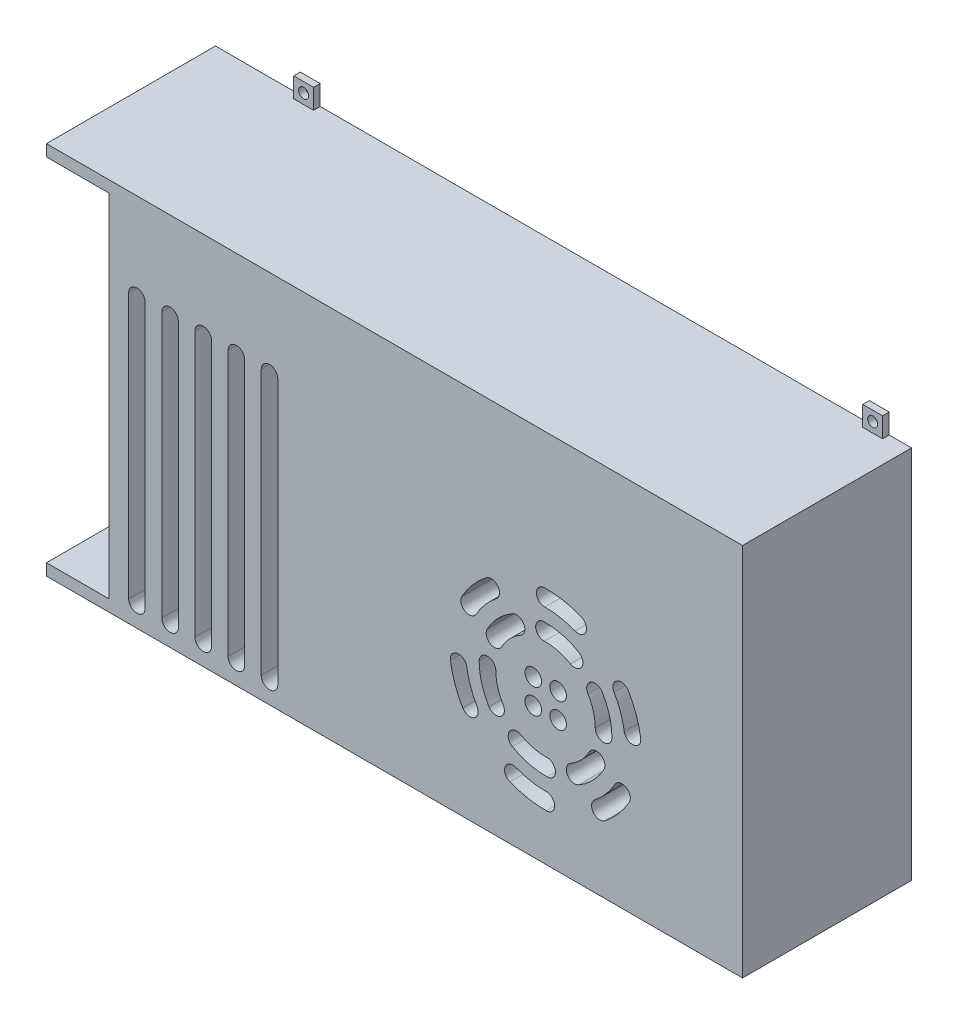
SolidWorks part; units mm, degrees
ref_plane "Plano frontal" through (0, 0, 0) normal (0, 0, 1) x (1, 0, 0)
ref_plane "Plano superior" through (0, 0, 0) normal (0, 1, 0) x (1, 0, 0)
ref_plane "Plano direito" through (0, 0, 0) normal (1, 0, 0) x (0, 0, -1)
sketch "Esboço1" plane through (0, 0, 0) normal (0, 0, 1) x (1, 0, 0)
  line L1 (-124.243, 56.5) -> (85.757, 56.5)
  line L2 (-124.243, 56.5) -> (-124.243, -56.5)
  line L3 (-124.243, -56.5) -> (85.757, -56.5)
  line L4 (85.757, 56.5) -> (85.757, -56.5)
  dimension "D1" = 210
  dimension "D2" = 56.5
  dimension "D3" = 56.5
extrude "Ressalto-extrusão1" add sketch "Esboço1" along normal blind 51
sketch "Esboço2" plane through (0, 0, 51) normal (0, 0, 1) x (1, 0, 0)
  arc A0 (33.8229, -0.4002) -> (25.9304, 1.6007) centre (26.3289, -13.394) ccw
  arc A1 (36.3349, 3.9553) -> (25.7969, 6.6268) centre (26.3289, -13.394) ccw
  arc A2 (35.2397, 8.8904) -> (26.1123, 10.605) centre (26.3289, -13.394) ccw
  arc A3 (37.0961, 13.533) -> (26.0672, 15.6048) centre (26.3289, -13.394) ccw
  arc A4 (25.7969, 6.6268) -> (25.9304, 1.6007) centre (25.8636, 4.1137) ccw
  arc A5 (33.8229, -0.4002) -> (36.3349, 3.9553) centre (35.0789, 1.7775) ccw
  arc A6 (41.3289, -13.3871) -> (39.1155, -5.5516) centre (26.3289, -13.394) ccw
  arc A7 (46.3568, -13.3848) -> (43.4014, -2.9228) centre (26.3289, -13.394) ccw
  arc A8 (43.4014, -2.9228) -> (39.1155, -5.5516) centre (41.2585, -4.2372) ccw
  arc A9 (41.3289, -13.3871) -> (46.3568, -13.3848) centre (43.8429, -13.386) ccw
  arc A10 (33.8349, -26.381) -> (39.514, -20.5463) centre (26.3289, -13.394) ccw
  arc A11 (36.3509, -30.7341) -> (43.9335, -22.9437) centre (26.3289, -13.394) ccw
  arc A12 (43.9335, -22.9437) -> (39.514, -20.5463) centre (41.7237, -21.745) ccw
  arc A13 (33.8349, -26.381) -> (36.3509, -30.7341) centre (35.0929, -28.5575) ccw
  arc A14 (18.8349, -26.3879) -> (26.7274, -28.3888) centre (26.3289, -13.394) ccw
  arc A15 (16.323, -30.7434) -> (26.861, -33.4149) centre (26.3289, -13.394) ccw
  arc A16 (26.861, -33.4149) -> (26.7274, -28.3888) centre (26.7942, -30.9018) ccw
  arc A17 (18.8349, -26.3879) -> (16.323, -30.7434) centre (17.5789, -28.5656) ccw
  arc A18 (11.3289, -13.401) -> (13.5424, -21.2365) centre (26.3289, -13.394) ccw
  arc A19 (6.301, -13.4033) -> (9.2564, -23.8653) centre (26.3289, -13.394) ccw
  arc A20 (9.2564, -23.8653) -> (13.5424, -21.2365) centre (11.3994, -22.5509) ccw
  arc A21 (11.3289, -13.401) -> (6.301, -13.4033) centre (8.815, -13.4021) ccw
  arc A22 (18.8229, -0.4071) -> (13.1439, -6.2418) centre (26.3289, -13.394) ccw
  arc A23 (16.307, 3.946) -> (8.7243, -3.8444) centre (26.3289, -13.394) ccw
  arc A24 (8.7243, -3.8444) -> (13.1439, -6.2418) centre (10.9341, -5.0431) ccw
  arc A25 (18.8229, -0.4071) -> (16.307, 3.946) centre (17.5649, 1.7694) ccw
  arc A26 (26.0672, 15.6048) -> (26.1123, 10.605) centre (26.0897, 13.1049) ccw
  arc A27 (35.2397, 8.8904) -> (37.0961, 13.533) centre (36.1679, 11.2117) ccw
  arc A28 (50.0832, -9.9688) -> (47.0044, -1.2069) centre (26.3289, -13.394) ccw
  arc A29 (55.0321, -9.2552) -> (51.3118, 1.332) centre (26.3289, -13.394) ccw
  arc A30 (51.3118, 1.332) -> (47.0044, -1.2069) centre (49.1581, 0.0625) ccw
  arc A31 (50.0832, -9.9688) -> (55.0321, -9.2552) centre (52.5576, -9.612) ccw
  arc A32 (41.1724, -32.2533) -> (47.221, -25.206) centre (26.3289, -13.394) ccw
  arc A33 (44.2648, -36.1823) -> (51.5735, -27.6668) centre (26.3289, -13.394) ccw
  arc A34 (51.5735, -27.6668) -> (47.221, -25.206) centre (49.3972, -26.4364) ccw
  arc A35 (41.1724, -32.2533) -> (44.2648, -36.1823) centre (42.7186, -34.2178) ccw
  arc A36 (17.4181, -35.6785) -> (26.5455, -37.3931) centre (26.3289, -13.394) ccw
  arc A37 (15.5617, -40.3211) -> (26.5907, -42.3929) centre (26.3289, -13.394) ccw
  arc A38 (26.5907, -42.3929) -> (26.5455, -37.3931) centre (26.5681, -39.893) ccw
  arc A39 (17.4181, -35.6785) -> (15.5617, -40.3211) centre (16.4899, -37.9998) ccw
  arc A40 (2.5746, -16.8193) -> (5.6535, -25.5811) centre (26.3289, -13.394) ccw
  arc A41 (-2.3742, -17.5329) -> (1.3461, -28.1201) centre (26.3289, -13.394) ccw
  arc A42 (1.3461, -28.1201) -> (5.6535, -25.5811) centre (3.4998, -26.8506) ccw
  arc A43 (2.5746, -16.8193) -> (-2.3742, -17.5329) centre (0.1002, -17.1761) ccw
  arc A44 (11.4854, 5.4652) -> (5.4369, -1.5821) centre (26.3289, -13.394) ccw
  arc A45 (8.393, 9.3942) -> (1.0843, 0.8787) centre (26.3289, -13.394) ccw
  arc A46 (1.0843, 0.8787) -> (5.4369, -1.5821) centre (3.2606, -0.3517) ccw
  arc A47 (11.4854, 5.4652) -> (8.393, 9.3942) centre (9.9392, 7.4297) ccw
  circle A48 centre (30.1279, -9.396) radius 2.5
  circle A49 centre (22.6279, -9.396) radius 2.5
  circle A50 centre (22.6279, -16.896) radius 2.5
  circle A51 centre (30.1279, -16.896) radius 2.5
  point P54 (26.3289, -13.394)
  point P89 (26.3289, -13.394)
  dimension "D1" = 6
  dimension "D3" = 7.5
  dimension "D4" = 7.5
  dimension "D2" = 6
extrude "Corte-extrusão1" cut sketch "Esboço2" against normal blind 51
sketch "Esboço3" plane through (0, 0, 51) normal (0, 0, 1) x (1, 0, 0)
  line L0 (-94.4411, 29.9352) -> (-94.4411, -50.0326)
  line L5 (-99.4411, -50.0326) -> (-99.4411, 29.9352)
  line L6 (-84.4411, 29.9352) -> (-84.4411, -50.0326)
  line L7 (-89.4411, -50.0326) -> (-89.4411, 29.9352)
  line L8 (-74.4411, 29.9352) -> (-74.4411, -50.0326)
  line L9 (-79.4411, -50.0326) -> (-79.4411, 29.9352)
  line L10 (-64.4411, 29.9352) -> (-64.4411, -50.0326)
  line L11 (-69.4411, -50.0326) -> (-69.4411, 29.9352)
  line L12 (-54.4411, 29.9352) -> (-54.4411, -50.0326)
  line L13 (-59.4411, -50.0326) -> (-59.4411, 29.9352)
  line L14 (-124.243, -56.5) -> (85.757, -56.5) construction
  arc A0 (-94.4411, 29.9352) -> (-99.4411, 29.9352) centre (-96.9411, 29.9352) ccw
  arc A1 (-99.4411, -50.0326) -> (-94.4411, -50.0326) centre (-96.9411, -50.0326) ccw
  arc A2 (-84.4411, 29.9352) -> (-89.4411, 29.9352) centre (-86.9411, 29.9352) ccw
  arc A3 (-89.4411, -50.0326) -> (-84.4411, -50.0326) centre (-86.9411, -50.0326) ccw
  arc A4 (-74.4411, 29.9352) -> (-79.4411, 29.9352) centre (-76.9411, 29.9352) ccw
  arc A5 (-79.4411, -50.0326) -> (-74.4411, -50.0326) centre (-76.9411, -50.0326) ccw
  arc A6 (-64.4411, 29.9352) -> (-69.4411, 29.9352) centre (-66.9411, 29.9352) ccw
  arc A7 (-69.4411, -50.0326) -> (-64.4411, -50.0326) centre (-66.9411, -50.0326) ccw
  arc A8 (-54.4411, 29.9352) -> (-59.4411, 29.9352) centre (-56.9411, 29.9352) ccw
  arc A9 (-59.4411, -50.0326) -> (-54.4411, -50.0326) centre (-56.9411, -50.0326) ccw
  dimension "D1" = 5
extrude "Corte-extrusão2" cut sketch "Esboço3" against normal blind 51
sketch "Esboço4" plane through (0, 0, 51) normal (0, 0, 1) x (1, 0, 0)
  line L0 (-124.243, 56.5) -> (-124.243, -56.5) construction
  line L1 (-124.243, 53) -> (-105.4059, 53)
  line L2 (-124.243, 53) -> (-124.243, -53)
  line L3 (-124.243, -53) -> (-105.4059, -53)
  line L4 (-105.4059, 53) -> (-105.4059, -53)
  line L6 (85.757, 56.5) -> (-124.243, 56.5) construction
  dimension "D1" = 3.5
  dimension "D2" = 106
extrude "Corte-extrusão3" cut sketch "Esboço4" against normal blind 39
ref_plane "Plano1" through (0, 0, 0) normal (0, 0, 1) x (1, 0, 0)
sketch "Esboço5" plane through (0, 0, 0) normal (0, 0, 1) x (1, 0, 0)
  line L0 (85.757, 56.5) -> (-124.243, 56.5) construction
  line L1 (-98.6537, 56.5) -> (-92.6537, 56.5)
  line L2 (-98.6537, 56.5) -> (-98.6537, 62.5)
  line L3 (-98.6537, 62.5) -> (-92.6537, 62.5)
  line L4 (-92.6537, 56.5) -> (-92.6537, 62.5)
  line L6 (73.0202, 56.5) -> (79.0202, 56.5)
  line L7 (73.0202, 56.5) -> (73.0202, 62.5)
  line L8 (73.0202, 62.5) -> (79.0202, 62.5)
  line L9 (79.0202, 56.5) -> (79.0202, 62.5)
  dimension "D1" = 6
  dimension "D2" = 6
  dimension "D3" = 6
  dimension "D4" = 6
extrude "Ressalto-extrusão2" add sketch "Esboço5" along normal blind 2
sketch "Esboço6" plane through (0, 0, 2) normal (0, 0, 1) x (1, 0, 0)
  line L0 (-92.6537, 56.5) -> (-92.6537, 62.5) construction
  line L1 (-92.6537, 62.5) -> (-98.6537, 62.5) construction
  circle A0 centre (-95.6537, 59.5) radius 1.5
  dimension "D1" = 3
  dimension "D2" = 3
  dimension "D3" = 3
extrude "Corte-extrusão4" cut sketch "Esboço6" against normal through all
sketch "Esboço7" plane through (0, 0, 2) normal (0, 0, 1) x (1, 0, 0)
  line L0 (79.0202, 56.5) -> (79.0202, 62.5) construction
  line L1 (79.0202, 62.5) -> (73.0202, 62.5) construction
  circle A0 centre (76.0202, 59.5) radius 1.5
  dimension "D1" = 3
  dimension "D2" = 3
  dimension "D3" = 3
extrude "Corte-extrusão5" cut sketch "Esboço7" against normal through all
sketch "Esboço8" plane through (0, 0, 0) normal (0, 0, 1) x (1, 0, 0)
  line L0 (-124.243, -56.5) -> (85.757, -56.5) construction
  line L1 (-98.653, -56.5) -> (-92.653, -56.5)
  line L2 (-98.653, -56.5) -> (-98.653, -62.5)
  line L3 (-98.653, -62.5) -> (-92.653, -62.5)
  line L4 (-92.653, -56.5) -> (-92.653, -62.5)
  line L5 (-124.243, -53) -> (-124.243, -56.5) construction
  line L7 (73.017, -56.5) -> (79.017, -56.5)
  line L8 (73.017, -56.5) -> (73.017, -62.5)
  line L9 (73.017, -62.5) -> (79.017, -62.5)
  line L10 (79.017, -56.5) -> (79.017, -62.5)
  point P8 (-124.243, -54.75)
  dimension "D1" = 25.59
  dimension "D2" = 6
  dimension "D3" = 6
  dimension "D4" = 6.74
  dimension "D5" = 6
  dimension "D6" = 6
extrude "Ressalto-extrusão3" add sketch "Esboço8" along normal blind 2
sketch "Esboço9" plane through (0, 0, 2) normal (0, 0, 1) x (1, 0, 0)
  line L0 (-92.653, -62.5) -> (-92.653, -56.5) construction
  line L1 (-124.243, -56.5) -> (85.757, -56.5) construction
  line L2 (73.017, -62.5) -> (79.017, -62.5) construction
  line L3 (73.017, -56.5) -> (73.017, -62.5) construction
  circle A0 centre (-95.653, -59.5) radius 1.5
  circle A1 centre (76.017, -59.5) radius 1.5
  dimension "D1" = 3
  dimension "D4" = 3
  dimension "D6" = 3
  dimension "D2" = 3
  dimension "D3" = 3
  dimension "D5" = 3
extrude "Corte-extrusão6" cut sketch "Esboço9" against normal through all
